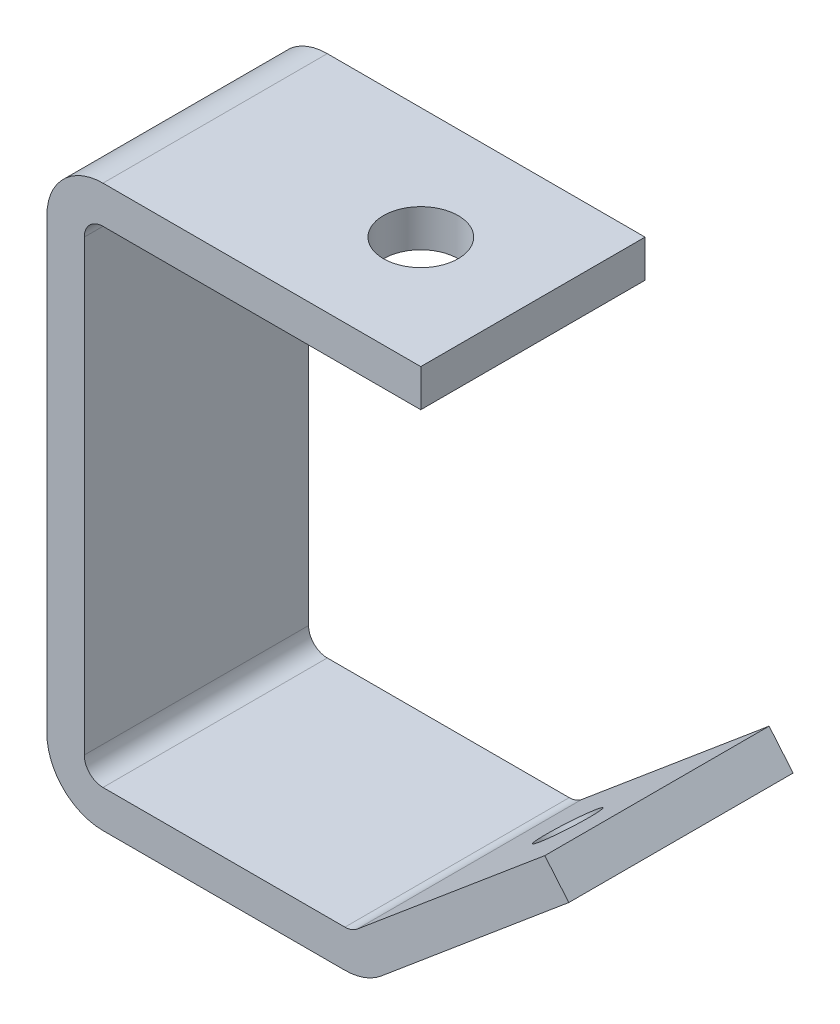
SolidWorks part; units mm, degrees
ref_plane "Front Plane" through (0, 0, 0) normal (0, 0, 1) x (1, 0, 0)
ref_plane "Top Plane" through (0, 0, 0) normal (0, 1, 0) x (1, 0, 0)
ref_plane "Right Plane" through (0, 0, 0) normal (1, 0, 0) x (0, 0, -1)
sketch "Sketch1" plane through (0, 0, 0) normal (0, 0, 1) x (1, 0, 0)
  line L0 (-3.4941, 0) -> (-44.59, 0)
  line L1 (-54.12, 9.53) -> (-54.12, 85.72)
  line L2 (-44.59, 95.25) -> (9.39, 95.25)
  line L3 (2.6766, 2.246) -> (34.5409, 28.9833)
  line L16 (-1.4051, 7.1104) -> (30.4592, 33.8477)
  line L17 (-3.4941, 6.35) -> (-44.59, 6.35)
  line L18 (-47.77, 9.53) -> (-47.77, 85.72)
  line L19 (-44.59, 88.9) -> (9.39, 88.9)
  line L20 (9.39, 95.25) -> (9.39, 88.9)
  line L21 (34.5409, 28.9833) -> (30.4592, 33.8477)
  arc A0 (-54.12, 85.72) -> (-44.59, 95.25) centre (-44.59, 85.72) cw
  arc A1 (-44.59, 0) -> (-54.12, 9.53) centre (-44.59, 9.53) cw
  arc A4 (-3.4941, 0) -> (2.6766, 2.246) centre (-3.4941, 9.6) ccw
  arc A5 (-3.4941, 6.35) -> (-1.4051, 7.1104) centre (-3.4941, 9.6) ccw
  arc A6 (-44.59, 6.35) -> (-47.77, 9.53) centre (-44.59, 9.53) cw
  arc A7 (-47.77, 85.72) -> (-44.59, 88.9) centre (-44.59, 85.72) cw
  point P14 (-54.12, 95.25)
  point P23 (0, 0)
  dimension "D7" = 9.53
  dimension "D8" = 9.6
  dimension "D1" = 54.12
  dimension "D2" = 45.09
  dimension "D3" = 140
  dimension "D4" = 63.51
  dimension "D5" = 95.25
  dimension "D6" = 6.35
extrude "Boss-Extrude1" add sketch "Sketch1" along normal mid plane 38.1
sketch "Sketch2" plane through (0, 95.25, 0) normal (0, 1, 0) x (1, 0, 0)
  line L1 (9.39, -19.05) -> (9.39, 19.05) construction
  circle A0 centre (-9.65, 0) radius 6.35
  dimension "D2" = 12.7
  dimension "D1" = 19.04
extrude "Cut-Extrude1" cut sketch "Sketch2" against normal blind 21.43
sketch "Sketch3" plane through (-4.0817, 4.8644, 0) normal (-0.6428, 0.766, 0) x (0.766, 0.6428, 0)
  line L0 (45.09, -19.05) -> (45.09, 19.05) construction
  circle A0 centre (25.29, 0) radius 4.765
  dimension "D1" = 9.53
  dimension "D2" = 19.8
extrude "Cut-Extrude2" cut sketch "Sketch3" against normal blind 46.1
